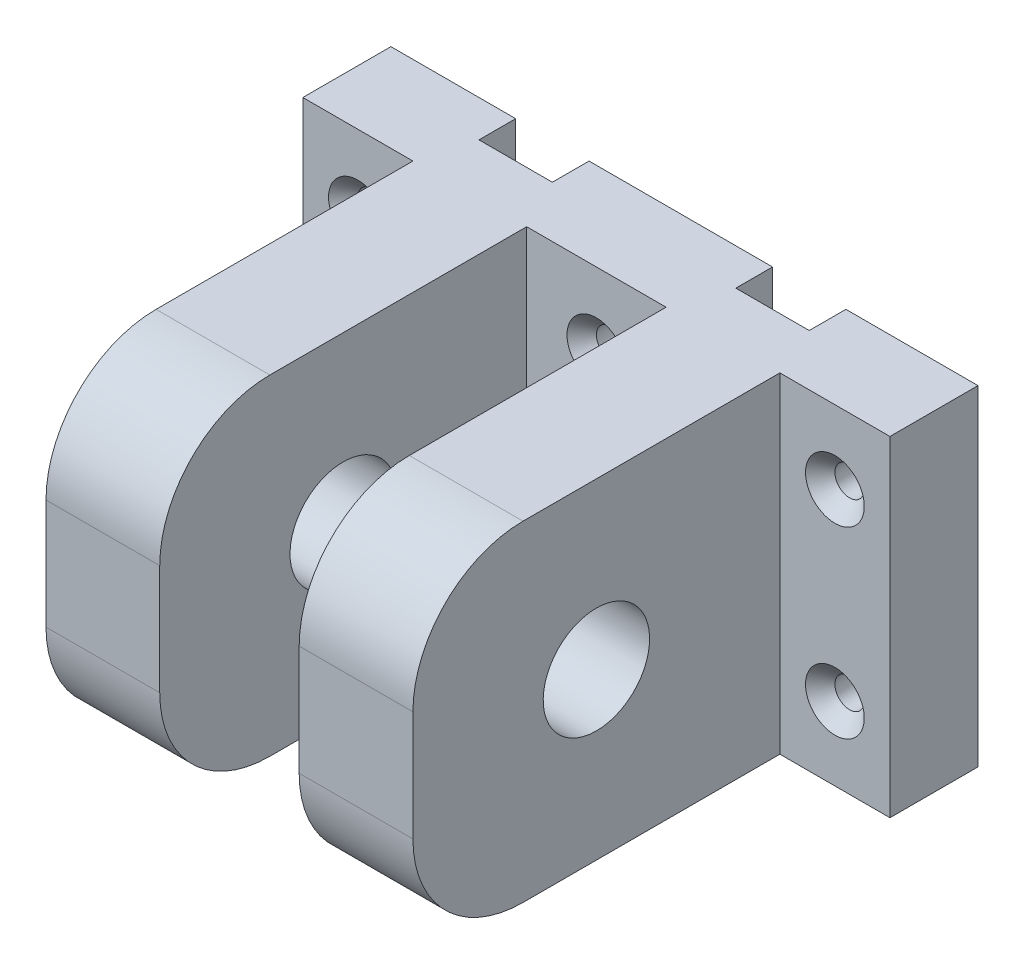
SolidWorks part; units mm, degrees
ref_plane "Front Plane" through (0, 0, 0) normal (0, 0, 1) x (1, 0, 0)
ref_plane "Top Plane" through (0, 0, 0) normal (0, 1, 0) x (1, 0, 0)
ref_plane "Right Plane" through (0, 0, 0) normal (1, 0, 0) x (0, 0, -1)
sketch "Sketch1" plane through (0, 0, 0) normal (0, 0, 1) x (1, 0, 0)
  line L1 (0, 0) -> (80, 0)
  line L2 (0, 0) -> (0, 45)
  line L3 (0, 45) -> (80, 45)
  line L4 (80, 0) -> (80, 45)
  dimension "D1" = 80
  dimension "D2" = 45
extrude "Boss-Extrude1" add sketch "Sketch1" along normal blind 12
sketch "Sketch2" plane through (0, 0, 12) normal (0, 0, 1) x (1, 0, 0)
  line L0 (80, 45) -> (0, 45) construction
  line L1 (15, 45) -> (30.5, 45)
  line L2 (15, 45) -> (15, 0)
  line L3 (15, 0) -> (30.5, 0)
  line L4 (30.5, 45) -> (30.5, 0)
  line L5 (0, 0) -> (80, 0) construction
  line L6 (0, 45) -> (0, 0) construction
  line L7 (49.5, 45) -> (65, 45)
  line L8 (49.5, 45) -> (49.5, 0)
  line L9 (49.5, 0) -> (65, 0)
  line L10 (65, 45) -> (65, 0)
  line L11 (80, 0) -> (80, 45) construction
  dimension "D1" = 15.5
  dimension "D2" = 15.5
  dimension "D3" = 15
  dimension "D4" = 15
extrude "Boss-Extrude2" add sketch "Sketch2" along normal blind 50
sketch "Sketch3" plane through (15, 0, 0) normal (-1, 0, 0) x (0, 0, 1)
  line L0 (62, 45) -> (12, 45) construction
  line L1 (12, 45) -> (12, 0) construction
  circle A0 centre (37, 22.5) radius 7.25
  dimension "D2" = 25
  dimension "D3" = 14.5
  dimension "D1" = 22.5
extrude "Cut-Extrude1" cut sketch "Sketch3" against normal blind 50
fillet "Fillet1" radius 15 4 edges at (22.75, 45, 62) (57.25, 45, 62) (22.75, 0, 62) (57.25, 0, 62)
sketch "Sketch5" plane through (0, 0, 12) normal (0, 0, 1) x (1, 0, 0)
  line L0 (15, 45) -> (0, 45) construction
  line L1 (0, 0) -> (15, 0) construction
  line L2 (49.5, 45) -> (30.5, 45) construction
  line L3 (30.5, 0) -> (49.5, 0) construction
  line L4 (65, 0) -> (80, 0) construction
  line L5 (0, 45) -> (0, 0) construction
  line L6 (80, 0) -> (80, 45) construction
  line L7 (80, 45) -> (65, 45) construction
  circle A0 centre (7.5, 35) radius 2
  circle A1 centre (7.5, 10) radius 2
  circle A2 centre (40, 35) radius 2
  circle A3 centre (40, 10) radius 2
  circle A4 centre (72.5, 35) radius 2
  circle A5 centre (72.5, 10) radius 2
  point P14 (7.5, 45)
  point P23 (40, 0)
  dimension "D1" = 4
  dimension "D2" = 4
  dimension "D3" = 4
  dimension "D4" = 4
  dimension "D5" = 4
  dimension "D6" = 4
  dimension "D7" = 10
  dimension "D8" = 10
  dimension "D9" = 10
  dimension "D10" = 10
  dimension "D11" = 10
  dimension "D13" = 7.5
  dimension "D14" = 7.5
  dimension "D15" = 40
  dimension "D16" = 40
  dimension "D17" = 10
  dimension "D18" = 7.5
  dimension "D19" = 7.5
  dimension "D12" = 10
extrude "Cut-Extrude2" cut sketch "Sketch5" against normal blind 50
chamfer "Chamfer1" distance 2 angle 45 6 edges at (74.5, 10, 12) (74.5, 35, 12) (42, 10, 12) (42, 35, 12) (9.5, 10, 12) (9.5, 35, 12)
sketch "Sketch6" plane through (0, 0, 0) normal (0, 0, -1) x (-1, 0, 0)
  line L0 (0, 45) -> (0, 0) construction
  line L1 (-17, -10.1708) -> (-27, -10.1708)
  line L2 (-17, -10.1708) -> (-17, 52.1549)
  line L3 (-17, 52.1549) -> (-27, 52.1549)
  line L4 (-27, -10.1708) -> (-27, 52.1549)
  line L5 (0, 0) -> (-80, 0) construction
  line L6 (-17, 12) -> (-27, 12)
  line L7 (-17, 12) -> (-17, 33)
  line L8 (-17, 33) -> (-27, 33)
  line L9 (-27, 12) -> (-27, 33)
  line L10 (-80, 45) -> (0, 45) construction
  line L12 (-52, -12.2336) -> (-62, -12.2336)
  line L13 (-52, -12.2336) -> (-52, 57.9012)
  line L14 (-52, 57.9012) -> (-62, 57.9012)
  line L15 (-62, -12.2336) -> (-62, 57.9012)
  line L16 (-52, 12) -> (-62, 12)
  line L17 (-52, 12) -> (-52, 33)
  line L18 (-52, 33) -> (-62, 33)
  line L19 (-62, 12) -> (-62, 33)
  point P22 (-57, 33)
  line M15 (0, 45) -> (-80, 45)
  line M17 (-80, 0) -> (0, 0)
  dimension "D1" = 17
  dimension "D2" = 27
  dimension "D3" = 12
  dimension "D4" = 12
  dimension "D5" = 52
  dimension "D6" = 62
  dimension "D7" = 12
  dimension "D8" = 12
extrude "Cut-Extrude3" cut sketch "Sketch6" against normal blind 5 contours L2 L6 L4 M17 | L13 L16 L15 M17 | L18 L13 L15 M15 | L8 L2 L4 M15
